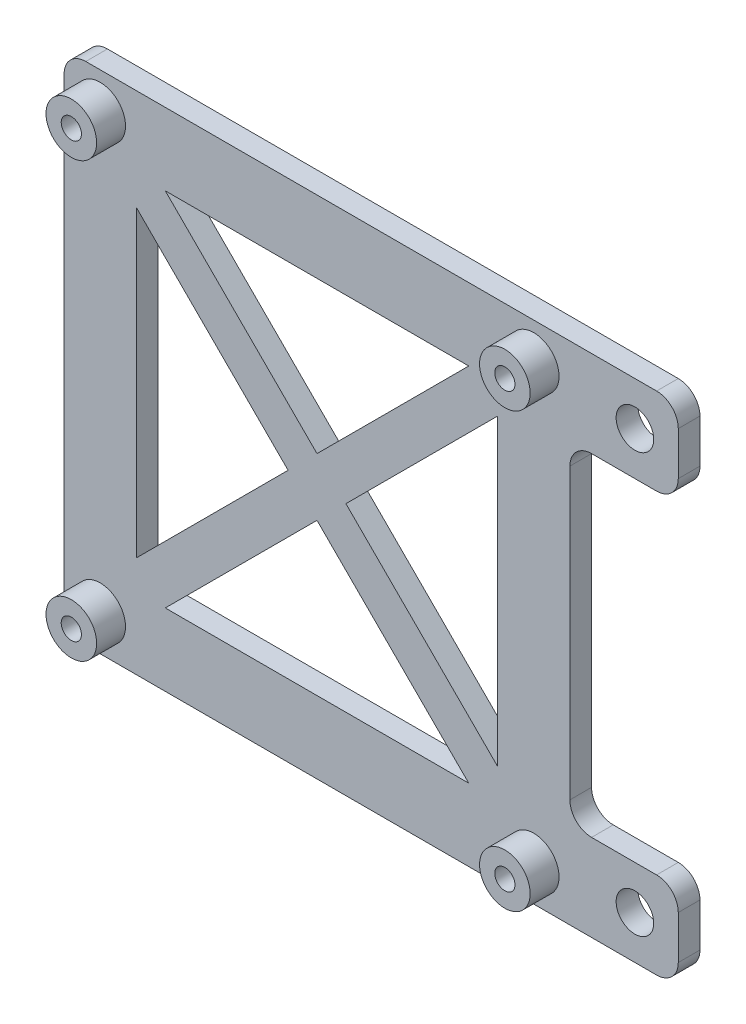
SolidWorks part; units mm, degrees
ref_plane "Front Plane" through (0, 0, 0) normal (0, 0, 1) x (1, 0, 0)
ref_plane "Top Plane" through (0, 0, 0) normal (0, 1, 0) x (1, 0, 0)
ref_plane "Right Plane" through (0, 0, 0) normal (1, 0, 0) x (0, 0, -1)
sketch "Sketch1" plane through (0, 0, 0) normal (0, 0, 1) x (1, 0, 0)
  line L1 (3, 0) -> (70, 0)
  line L2 (0, 3) -> (0, 67)
  line L3 (3, 70) -> (67, 70)
  line L4 (70, 15) -> (70, 55)
  line L5 (67, 70) -> (82, 70)
  line L7 (73, 58) -> (82, 58)
  line L8 (85, 67) -> (85, 61)
  line L9 (70, 0) -> (82, 0)
  line L11 (73, 12) -> (82, 12)
  line L12 (85, 3) -> (85, 9)
  arc A0 (3, 70) -> (0, 67) centre (3, 67) ccw
  arc A1 (0, 3) -> (3, 0) centre (3, 3) ccw
  arc A2 (85, 3) -> (82, 0) centre (82, 3) cw
  arc A3 (85, 9) -> (82, 12) centre (82, 9) ccw
  arc A4 (73, 12) -> (70, 15) centre (73, 15) cw
  arc A5 (82, 70) -> (85, 67) centre (82, 67) cw
  arc A6 (85, 61) -> (82, 58) centre (82, 61) cw
  arc A7 (73, 58) -> (70, 55) centre (73, 55) ccw
  circle A8 centre (79, 64) radius 2.6
  circle A9 centre (79, 6) radius 2.6
  point P13 (0, 70)
  point P16 (0, 0)
  point P25 (85, 70)
  point P28 (85, 58)
  point P31 (85, 64)
  point P38 (85, 6)
  dimension "D4" = 3
  dimension "D6" = 5.2
  dimension "D1" = 70
  dimension "D2" = 15
  dimension "D3" = 12
  dimension "D5" = 70
  dimension "D7" = 6
  dimension "D8" = 9
extrude "Boss-Extrude1" add sketch "Sketch1" along normal blind 3
sketch "Sketch2" plane through (0, 0, 3) normal (0, 0, 1) x (1, 0, 0)
  line L0 (0, 67) -> (0, 3) construction
  line L1 (5, 65) -> (65, 65) construction
  line L2 (5, 65) -> (5, 5) construction
  line L3 (5, 5) -> (65, 5) construction
  line L4 (65, 65) -> (65, 5) construction
  line L5 (0, 67) -> (0, 3) construction
  circle A0 centre (5, 65) radius 3.5
  circle A1 centre (65, 65) radius 3.5
  circle A2 centre (65, 5) radius 3.5
  circle A3 centre (5, 5) radius 3.5
  point P6 (0, 35)
  point P7 (5, 35)
  dimension "D3" = 7
  dimension "D1" = 60
  dimension "D2" = 5
extrude "Boss-Extrude2" add sketch "Sketch2" along normal blind 4
sketch "Sketch3" plane through (0, 0, 3) normal (0, 0, 1) x (1, 0, 0)
  line L0 (14, 60) -> (56, 60)
  line L5 (35, 39) -> (35, 35) construction
  line L6 (56, 60) -> (35, 39)
  line L19 (35, 39) -> (14, 60)
  line L20 (82, 70) -> (3, 70) construction
  line L21 (0, 67) -> (0, 3) construction
  line L22 (60, 56) -> (60, 14)
  line L23 (70, 15) -> (70, 55) construction
  line L24 (39, 35) -> (60, 56)
  line L25 (60, 14) -> (39, 35)
  line L26 (56, 10) -> (14, 10)
  line L27 (35, 31) -> (56, 10)
  line L28 (14, 10) -> (35, 31)
  line L29 (10, 14) -> (10, 56)
  line L30 (31, 35) -> (10, 14)
  line L31 (10, 56) -> (31, 35)
  point P5 (0, 35)
  point P6 (35, 60)
  point P24 (35, 35)
  dimension "D1" = 10
  dimension "D2" = 14
  dimension "D3" = 14
  dimension "D4" = 4
  dimension "D5" = 4
extrude "Cut-Extrude1" cut sketch "Sketch3" against normal blind 3
sketch "Sketch4" plane through (0, 0, 7) normal (0, 0, 1) x (1, 0, 0)
  circle A0 centre (5, 65) radius 1.4
  circle A1 centre (65, 65) radius 1.4
  circle A2 centre (65, 5) radius 1.4
  circle A3 centre (5, 5) radius 1.4
  dimension "D1" = 2.8
extrude "Cut-Extrude2" cut sketch "Sketch4" against normal through all
